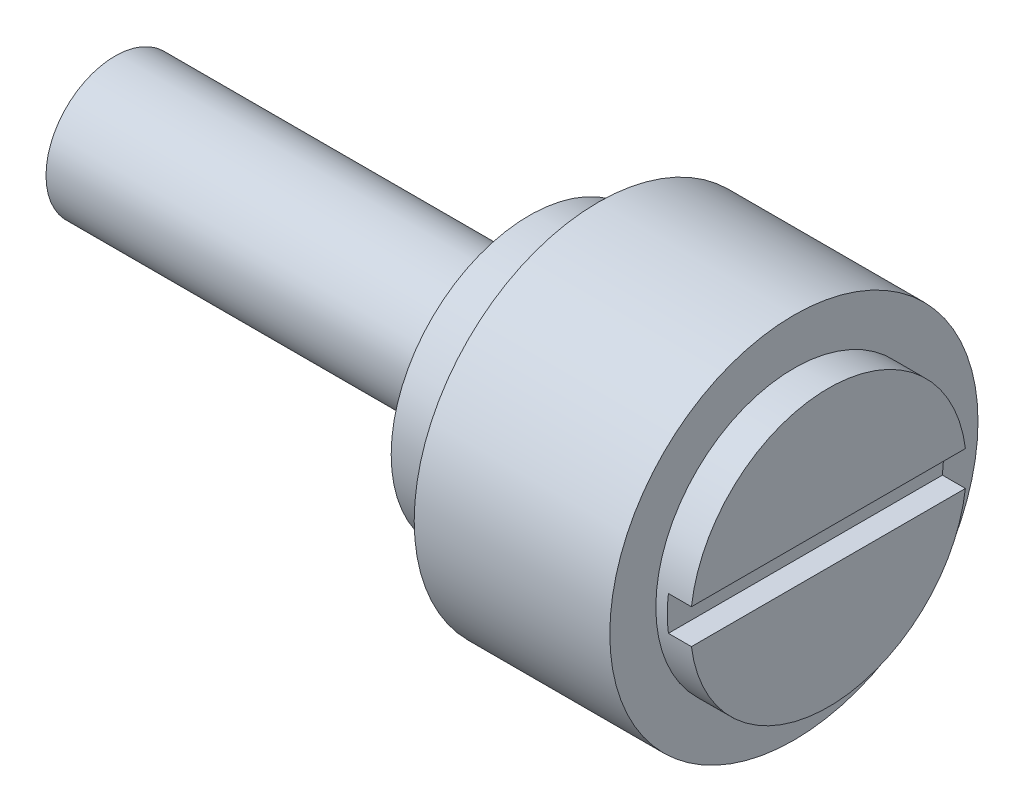
SolidWorks part; units mm, degrees
ref_plane "Спереди" through (0, 0, 0) normal (0, 0, 1) x (1, 0, 0)
ref_plane "Сверху" through (0, 0, 0) normal (0, 1, 0) x (1, 0, 0)
ref_plane "Справа" through (0, 0, 0) normal (1, 0, 0) x (0, 0, -1)
sketch "Эскиз1" plane through (0, 0, 0) normal (0, 0, 1) x (1, 0, 0)
  line L0 (0, 0) -> (0, 3)
  line L1 (0, 3) -> (18, 3)
  line L2 (18, 3) -> (18, 6)
  line L3 (18, 6) -> (21, 6)
  line L4 (21, 6) -> (21, 8)
  line L5 (21, 8) -> (29.5, 8)
  line L6 (29.5, 8) -> (29.5, 6)
  line L7 (29.5, 6) -> (31, 6)
  line L8 (31, 6) -> (31, 0)
  line L9 (0, 0) -> (31, 0) construction
  line L10 (0, 0) -> (31, 0)
  dimension "l" = 31
  dimension "l3" = 1.5
  dimension "S" = 3
  dimension "l5" = 10
  dimension "d1" = 6
  dimension "d3" = 12
  dimension "D5" = 12
  dimension "D" = 16
revolve "Повернуть1" add sketch "Эскиз1" angle 360 about L9
sketch "Эскиз2" plane through (31, 0, 0) normal (1, 0, 0) x (0, 0, -1)
  line L0 (-8, 0.75) -> (8, 0.75)
  line L1 (8, 0.75) -> (8, -0.75)
  line L2 (8, -0.75) -> (-8, -0.75)
  line L3 (-8, -0.75) -> (-8, 0.75)
  line L4 (-8, 0) -> (8, 0) construction
  dimension "b1" = 1.5
  dimension "D" = 16
extrude "Вырез-Вытянуть1" cut sketch "Эскиз2" against normal blind 1
